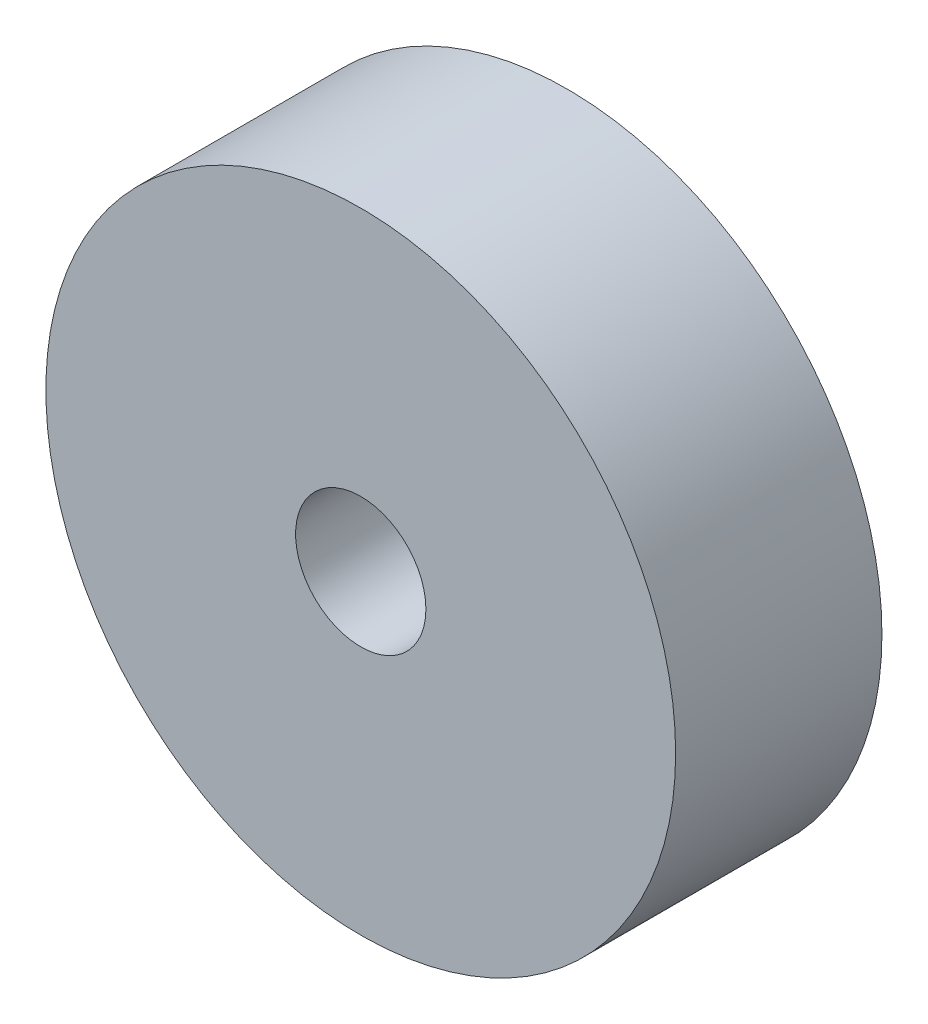
SolidWorks part; units mm, degrees
ref_plane "Front Plane" through (0, 0, 0) normal (0, 0, 1) x (1, 0, 0)
ref_plane "Top Plane" through (0, 0, 0) normal (0, 1, 0) x (1, 0, 0)
ref_plane "Right Plane" through (0, 0, 0) normal (1, 0, 0) x (0, 0, -1)
sketch "Sketch1" plane through (0, 0, 0) normal (0, 0, 1) x (1, 0, 0)
  circle A0 centre (0, 0) radius 29
  dimension "D1" = 58
extrude "Boss-Extrude1" add sketch "Sketch1" along normal blind 19
sketch "Sketch2" plane through (0, 0, 19) normal (0, 0, 1) x (1, 0, 0)
  circle A0 centre (0, 0) radius 6
  dimension "D1" = 12
extrude "Cut-Extrude1" cut sketch "Sketch2" against normal blind 19
